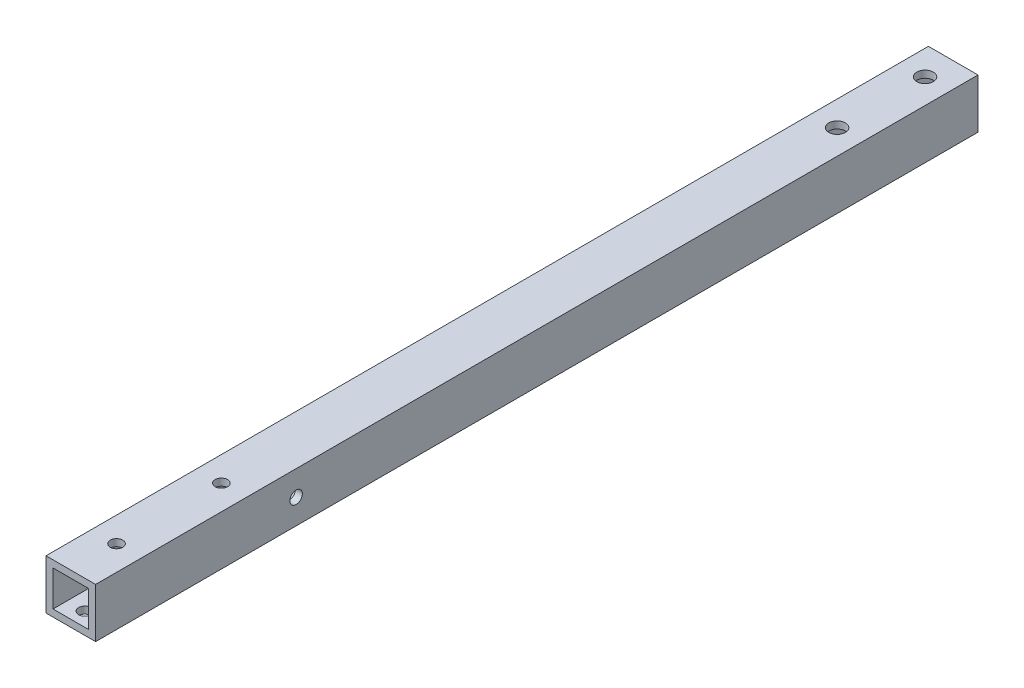
SolidWorks part; units mm, degrees
ref_plane "Front Plane" through (0, 0, 0) normal (0, 0, 1) x (1, 0, 0)
ref_plane "Top Plane" through (0, 0, 0) normal (0, 1, 0) x (1, 0, 0)
ref_plane "Right Plane" through (0, 0, 0) normal (1, 0, 0) x (0, 0, -1)
sketch "Sketch1" plane through (0, 0, 0) normal (0, 0, 1) x (1, 0, 0)
  line L1 (19.997, 25.6895) -> (34.097, 25.6895)
  line L2 (19.997, 25.6895) -> (19.997, 11.5895)
  line L3 (19.997, 11.5895) -> (34.097, 11.5895)
  line L4 (34.097, 25.6895) -> (34.097, 11.5895)
  dimension "D1" = 14.1
extrude "Boss-Extrude1" add sketch "Sketch1" along normal blind 250.825
sketch "Sketch2" plane through (0, 0, 250.825) normal (0, 0, 1) x (1, 0, 0)
  line L0 (19.997, 25.6895) -> (19.997, 11.5895) construction
  line L1 (21.997, 23.6895) -> (32.097, 23.6895)
  line L2 (21.997, 23.6895) -> (21.997, 13.5895)
  line L3 (21.997, 13.5895) -> (32.097, 13.5895)
  line L4 (32.097, 23.6895) -> (32.097, 13.5895)
  line L5 (34.097, 25.6895) -> (19.997, 25.6895) construction
  line L6 (34.097, 11.5895) -> (34.097, 25.6895) construction
  dimension "D1" = 2
  dimension "D2" = 2
  dimension "D3" = 2
extrude "Cut-Extrude1" cut sketch "Sketch2" against normal through all
sketch "Sketch3" plane through (0, 11.5895, 0) normal (0, -1, 0) x (1, 0, 0)
  line L0 (27.047, 250.825) -> (27.047, 0) construction
  line L1 (19.997, 250.825) -> (34.097, 250.825) construction
  line L2 (19.997, 0) -> (34.097, 0) construction
  circle A1 centre (27.047, 237.825) radius 1.775
  circle A2 centre (27.047, 208.025) radius 1.775
  circle A3 centre (27.047, 8) radius 2.3587
  circle A4 centre (27.047, 33) radius 2.3587
  dimension "D1" = 250.825
  dimension "D3" = 13
  dimension "D5" = 29.8
  dimension "D6" = 8
  dimension "D7" = 33
extrude "Cut-Extrude2" cut sketch "Sketch3" against normal through all
sketch "Sketch4" plane through (0, 11.5895, 0) normal (0, -1, 0) x (1, 0, 0)
  line L0 (27.047, 246.825) -> (27.047, 237.825) construction
  line L1 (19.997, 250.825) -> (34.097, 250.825) construction
  line L2 (27.047, 250.825) -> (27.047, 221.5198) construction
  circle A0 centre (27.047, 246.825) radius 1.775
  dimension "D1" = 3.55
  dimension "D2" = 4
extrude "Cut-Extrude3" cut sketch "Sketch4" against normal up to surface (2 mm away) up to face at (27.047, 13.5895, 30.6413)
sketch "Sketch5" plane through (34.097, 0, 0) normal (1, 0, 0) x (0, 0, -1)
  line L0 (-250.825, 18.6395) -> (-163.1913, 18.6395) construction
  line L1 (-250.825, 11.5895) -> (-250.825, 25.6895) construction
  circle A0 centre (-193.825, 18.6395) radius 1.775
  dimension "D1" = 3.55
  dimension "D2" = 57
extrude "Cut-Extrude4" cut sketch "Sketch5" against normal through all
